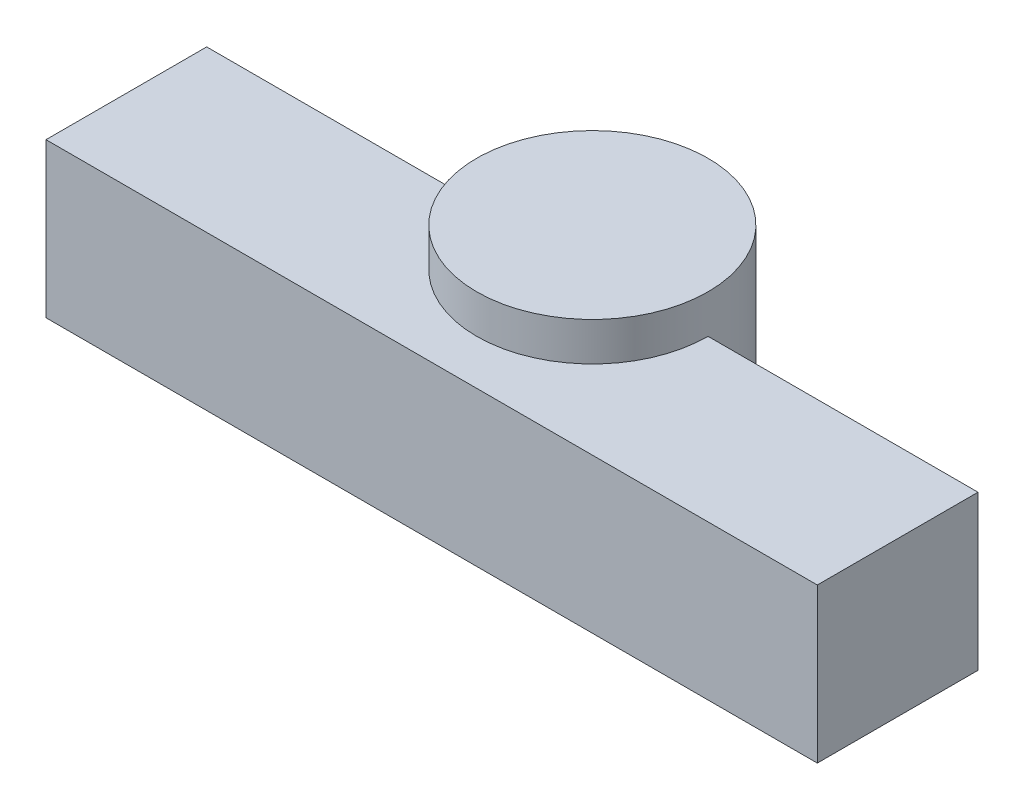
SolidWorks part; units mm, degrees
ref_plane "前视基准面" through (0, 0, 0) normal (0, 0, 1) x (1, 0, 0)
ref_plane "上视基准面" through (0, 0, 0) normal (0, 1, 0) x (1, 0, 0)
ref_plane "右视基准面" through (0, 0, 0) normal (1, 0, 0) x (0, 0, -1)
other "Configuration Table"
sketch "草图1" plane through (0, 0, 0) normal (0, 0, 1) x (1, 0, 0)
  line L1 (-60000, 0) -> (60000, 0)
  line L2 (-60000, 0) -> (-60000, 24000)
  line L3 (-60000, 24000) -> (60000, 24000)
  line L4 (60000, 0) -> (60000, 24000)
extrude "凸台-拉伸1" add sketch "草图1" along normal blind 25000
sketch "草图2" plane through (0, 0, 0) normal (0, 1, 0) x (1, 0, 0)
  circle A0 centre (0, 0) radius 18000
extrude "凸台-拉伸2" add sketch "草图2" along normal blind 30000
